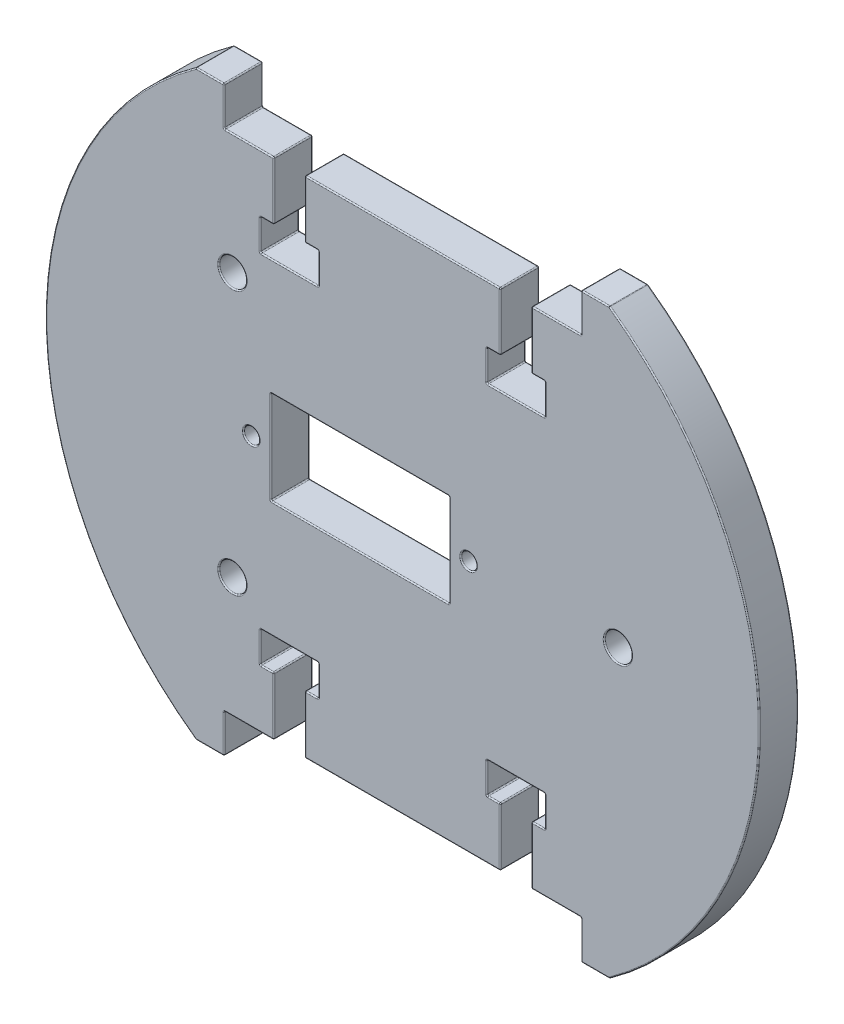
SolidWorks part; units mm, degrees
ref_plane "Front Plane" through (0, 0, 0) normal (0, 0, 1) x (1, 0, 0)
ref_plane "Top Plane" through (0, 0, 0) normal (0, 1, 0) x (1, 0, 0)
ref_plane "Right Plane" through (0, 0, 0) normal (1, 0, 0) x (0, 0, -1)
sketch "Sketch1" plane through (0, 0, 0) normal (0, 0, 1) x (1, 0, 0)
  line L0 (-26.6411, 37.5) -> (-23, 37.5)
  line L1 (23, 37.5) -> (26.6411, 37.5)
  line L2 (0, 0) -> (-46.9692, 0) construction
  line L3 (-23, 37.5) -> (-23, 32.5)
  line L4 (-23, 32.5) -> (23, 32.5)
  line L5 (23, 37.5) -> (23, 32.5)
  line L6 (23, -37.5) -> (26.6411, -37.5)
  line L7 (23, -37.5) -> (23, -32.5)
  line L8 (-23, -32.5) -> (23, -32.5)
  line L9 (-23, -37.5) -> (-23, -32.5)
  line L10 (-26.6411, -37.5) -> (-23, -37.5)
  line L11 (27.75, 0) -> (-21.93, 0) construction
  line L12 (-17, 6) -> (6, 6)
  line L13 (-17, 6) -> (-17, -6)
  line L14 (-17, -6) -> (6, -6)
  line L15 (6, 6) -> (6, -6)
  line L16 (-17, 6) -> (6, -6) construction
  line L17 (-17, -6) -> (6, 6) construction
  line L18 (-21.93, 17) -> (-21.93, -17) construction
  arc A0 (-26.6411, 37.5) -> (-26.6411, -37.5) centre (0, 0) ccw
  arc A1 (26.6411, -37.5) -> (26.6411, 37.5) centre (0, 0) ccw
  circle A2 centre (-19.5, 0) radius 1
  circle A3 centre (8.5, 0) radius 1
  circle A4 centre (-21.93, 17) radius 1.75
  circle A5 centre (-21.93, -17) radius 1.75
  circle A6 centre (27.75, 0) radius 1.75
  point P9 (0, 32.5)
  point P16 (-5.5, 0)
  point P29 (-21.93, 0)
  dimension "D1" = 92
  dimension "D8" = 2
  dimension "D9" = 2
  dimension "D15" = 3.5
  dimension "D2" = 37.5
  dimension "D3" = 5
  dimension "D4" = 46
  dimension "D5" = 6
  dimension "D6" = 23
  dimension "D7" = 12
  dimension "D10" = 2.5
  dimension "D11" = 2.5
  dimension "D12" = 34
  dimension "D13" = 27.75
  dimension "D14" = 49.68
sketch "Sketch2" plane through (0, 0, 0) normal (0, 0, 1) x (1, 0, 0)
extrude "Boss-Extrude1" add sketch "Sketch1" along normal blind 5
sketch "Sketch4" plane through (0, 0, 5) normal (0, 0, 1) x (1, 0, 0)
  line L0 (23, 32.5) -> (-23, 32.5) construction
  line L1 (-12.6, 25) -> (-16.6, 25)
  line L2 (-12.6, 25) -> (-12.6, 32.5)
  line L3 (-12.6, 32.5) -> (-16.6, 32.5)
  line L4 (-16.6, 25) -> (-16.6, 32.5)
  line L5 (-12.6, 25) -> (-16.6, 32.5) construction
  line L6 (-12.6, 32.5) -> (-16.6, 25) construction
  line L7 (-23, 32.5) -> (-23, 37.5) construction
  line L8 (-10.85, 21) -> (-18.35, 21)
  line L9 (-10.85, 21) -> (-10.85, 25)
  line L10 (-10.85, 25) -> (-18.35, 25)
  line L11 (-18.35, 21) -> (-18.35, 25)
  line L12 (-10.85, 21) -> (-18.35, 25) construction
  line L13 (-10.85, 25) -> (-18.35, 21) construction
  line L14 (-25.6594, 0) -> (0, 0) construction
  line L15 (0, 0) -> (0, 30.9773) construction
  line L16 (10.85, 25) -> (18.35, 21) construction
  line L17 (10.85, 21) -> (18.35, 25) construction
  line L18 (12.6, 32.5) -> (16.6, 25) construction
  line L19 (12.6, 25) -> (16.6, 32.5) construction
  line L20 (18.35, 21) -> (18.35, 25)
  line L21 (10.85, 25) -> (18.35, 25)
  line L22 (10.85, 21) -> (10.85, 25)
  line L23 (10.85, 21) -> (18.35, 21)
  line L24 (16.6, 25) -> (16.6, 32.5)
  line L25 (12.6, 32.5) -> (16.6, 32.5)
  line L26 (12.6, 25) -> (12.6, 32.5)
  line L27 (12.6, 25) -> (16.6, 25)
  line L28 (12.6, -25) -> (16.6, -32.5) construction
  line L29 (12.6, -32.5) -> (16.6, -25) construction
  line L30 (10.85, -21) -> (18.35, -25) construction
  line L31 (10.85, -25) -> (18.35, -21) construction
  line L32 (-10.85, -25) -> (-18.35, -21) construction
  line L33 (-10.85, -21) -> (-18.35, -25) construction
  line L34 (-12.6, -32.5) -> (-16.6, -25) construction
  line L35 (-12.6, -25) -> (-16.6, -32.5) construction
  line L36 (12.6, -25) -> (16.6, -25)
  line L37 (12.6, -25) -> (12.6, -32.5)
  line L38 (12.6, -32.5) -> (16.6, -32.5)
  line L39 (16.6, -25) -> (16.6, -32.5)
  line L40 (10.85, -21) -> (18.35, -21)
  line L41 (10.85, -21) -> (10.85, -25)
  line L42 (10.85, -25) -> (18.35, -25)
  line L43 (18.35, -21) -> (18.35, -25)
  line L44 (-18.35, -21) -> (-18.35, -25)
  line L45 (-10.85, -25) -> (-18.35, -25)
  line L46 (-10.85, -21) -> (-10.85, -25)
  line L47 (-10.85, -21) -> (-18.35, -21)
  line L48 (-16.6, -25) -> (-16.6, -32.5)
  line L49 (-12.6, -32.5) -> (-16.6, -32.5)
  line L50 (-12.6, -25) -> (-12.6, -32.5)
  line L51 (-12.6, -25) -> (-16.6, -25)
  point P0 (-14.6, 28.75)
  point P7 (-14.6, 23)
  point P26 (14.6, 23)
  point P27 (14.6, 28.75)
  point P44 (14.6, -28.75)
  point P45 (14.6, -23)
  point P46 (-14.6, -23)
  point P47 (-14.6, -28.75)
  line M12 (23, 32.5) -> (-23, 32.5)
  line M18 (-23, -32.5) -> (23, -32.5)
  dimension "D1" = 6.4
  dimension "D2" = 4
  dimension "D3" = 7.5
  dimension "D4" = 4
  dimension "D5" = 7.5
extrude "Cut-Extrude1" cut sketch "Sketch4" against normal through all contours L11 L8 L9 L10 L1 | L22 L23 L20 L21 | L26 L21 L24 M12 | L39 L36 L37 M18 | L43 L40 L41 L42 L36 | L46 L45 L44 L47 | L48 L49 L50 L51
fillet "Fillet1" radius 0.15 123 edges at (-18.35, 25, 2.5) (-10.85, 25, 2.5) (-10.85, 21, 2.5) (-10.85, 23, 0) (-10.85, 23, 5) (-14.6, 21, 5) (-18.35, 23, 5) (-16.6, 32.5, 2.5) (-12.6, 32.5, 2.5) (12.6, 25, 2.5) (12.6, 32.5, 2.5) (16.6, 25, 2.5) (18.35, 25, 2.5) (18.35, 21, 2.5) (10.85, 21, 2.5) (11.725, 25, 0) (12.6, 28.75, 0) (16.6, 28.75, 0) (17.475, 25, 0) (18.35, 23, 0) (14.6, 21, 0) (10.85, 23, 0) (12.6, 28.75, 5) (17.475, 25, 5) (18.35, 23, 5) (16.6, -32.5, 2.5) (12.6, -25, 2.5) (10.85, -25, 2.5) (10.85, -21, 2.5) (18.35, -21, 2.5) (18.35, -25, 2.5) (16.6, -25, 2.5) (12.6, -28.75, 0) (11.725, -25, 0) (10.85, -23, 0) (14.6, -21, 0) (18.35, -23, 0) (17.475, -25, 0) (11.725, -25, 5) (10.85, -23, 5) (14.6, -21, 5) (18.35, -23, 5) (17.475, -25, 5) (16.6, -28.75, 5) (-16.6, -32.5, 2.5) (-14.6, -21, 5) (-18.35, -23, 5) (-10.85, -23, 5) (-18.35, -23, 0) (-10.85, -23, 0) (-18.35, -21, 2.5) (-18.35, -25, 2.5) (-10.85, -25, 2.5) (-10.85, -21, 2.5) (-20.18, -17, 0) (-20.18, -17, 5) (-20.18, 17, 0) (-20.18, 17, 5) (9.5, 0, 0) (9.5, 0, 5) (6, 0, 0) (-5.5, 6, 0) (-17, 0, 0) (-5.5, -6, 0) (6, 0, 5) (-5.5, 6, 5) (-17, 0, 5) (-5.5, -6, 5) (6, -6, 2.5) (-17, 6, 2.5) (6, 6, 2.5) (23, -35, 0) (24.8206, -37.5, 0) (46, 0, 0) (23, 35, 0) (-19.8, 32.5, 0) (0, 32.5, 0) (19.8, 32.5, 0) (-23, 35, 0) (-24.8206, 37.5, 0) (-46, 0, 0) (-24.8206, -37.5, 0) (0, -32.5, 0) (-19.8, -32.5, 0) (24.8206, -37.5, 5) (46, 0, 5) (24.8206, 37.5, 5) (23, 35, 5) (0, 32.5, 5) (19.8, 32.5, 5) (-23, 35, 5) (-24.8206, 37.5, 5) (-46, 0, 5) (-23, -35, 5) (19.8, -32.5, 5) (0, -32.5, 5) (-19.8, -32.5, 5) (-23, -37.5, 2.5) (-26.6411, -37.5, 2.5) (-26.6411, 37.5, 2.5) (-23, 32.5, 2.5) (23, 32.5, 2.5) (26.6411, 37.5, 2.5) (26.6411, -37.5, 2.5) (23, -37.5, 2.5) (12.6, -32.5, 2.5)
